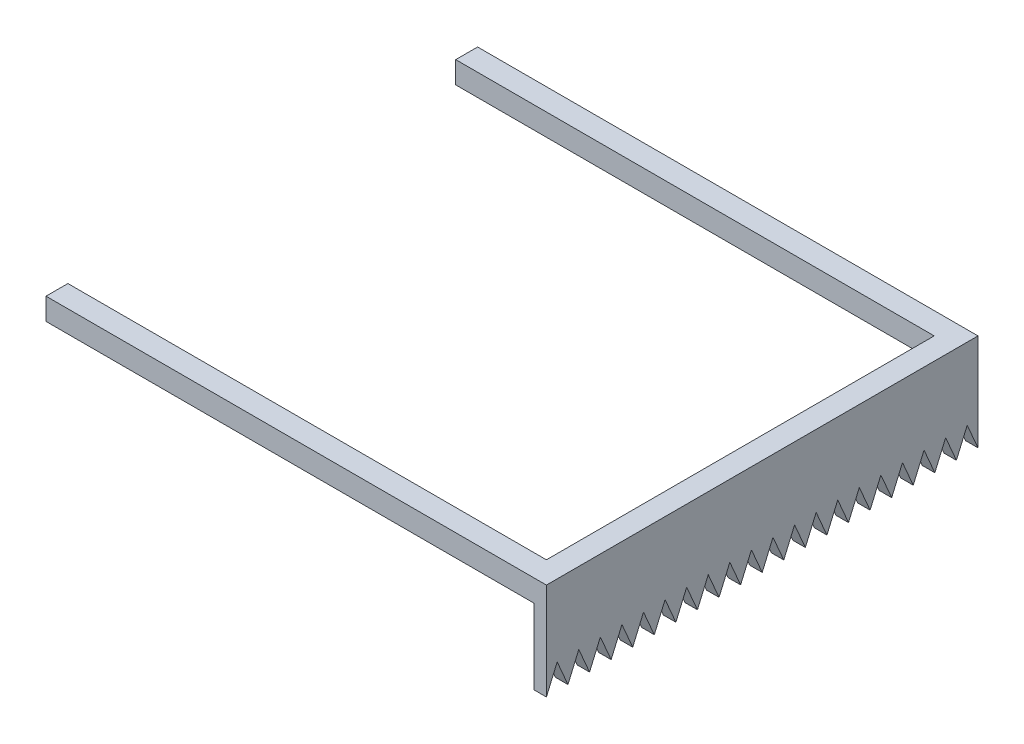
SolidWorks part; units mm, degrees
ref_plane "Front Plane" through (0, 0, 0) normal (0, 0, 1) x (1, 0, 0)
ref_plane "Top Plane" through (0, 0, 0) normal (0, 1, 0) x (1, 0, 0)
ref_plane "Right Plane" through (0, 0, 0) normal (1, 0, 0) x (0, 0, -1)
sketch "Sketch2" plane through (0, 0, 0) normal (1, 0, 0) x (0, 0, -1)
  line L0 (0, 35) -> (0, 0) construction
  line L1 (0, 0) -> (35, 0)
  line L2 (0, 0) -> (0, 35)
  line L3 (0, 35) -> (35, 35)
  line L4 (35, 0) -> (35, 35)
extrude "Boss-Extrude1" add sketch "Sketch2" along normal blind 800
sketch "Sketch3" plane through (0, 0, -35) normal (0, 0, -1) x (-1, 0, 0)
  line L0 (-800, 0) -> (0, 0) construction
  line L1 (-800, 35) -> (-765, 35)
  line L2 (-800, 35) -> (-800, 0)
  line L3 (-800, 0) -> (-765, 0)
  line L4 (-765, 35) -> (-765, 0)
extrude "Boss-Extrude2" add sketch "Sketch3" along normal up to surface (620 mm away)
sketch "Sketch5" plane through (800, 0, 0) normal (1, 0, 0) x (0, 0, -1)
  line L0 (655, 35) -> (0, 35) construction
  line L1 (655, 0) -> (690, 0)
  line L2 (655, 0) -> (655, 35)
  line L3 (655, 35) -> (690, 35)
  line L4 (690, 0) -> (690, 35)
extrude "Boss-Extrude3" add sketch "Sketch5" against normal up to surface (800 mm away) up to face at (0, 17.5, -17.5)
sketch "Sketch6" plane through (0, 0, 0) normal (0, -1, 0) x (1, 0, 0)
  line L0 (0, -690) -> (800, -690) construction
  line L1 (800, 0) -> (780, 0)
  line L2 (800, 0) -> (800, -690)
  line L3 (800, -690) -> (780, -690)
  line L4 (780, 0) -> (780, -690)
  dimension "D1" = 20
extrude "Boss-Extrude4" add sketch "Sketch6" along normal blind 120
sketch "Sketch7" plane through (800, 0, 0) normal (1, 0, 0) x (0, 0, -1)
  line L0 (0, -120) -> (17.25, -80)
  line L1 (17.25, -80) -> (34.5, -120)
  line L2 (690, -120) -> (0, -120) construction
  line L3 (34.5, -120) -> (0, -120)
  line L4 (0, -120) -> (690, -120) construction
  line L5 (17.25, -80) -> (17.25, -120) construction
  line L6 (34.5, -120) -> (51.75, -80)
  line L7 (51.75, -80) -> (69, -120)
  line L8 (69, -120) -> (34.5, -120)
  line L9 (69, -120) -> (86.25, -80)
  line L10 (86.25, -80) -> (103.5, -120)
  line L11 (103.5, -120) -> (69, -120)
  line L12 (103.5, -120) -> (120.75, -80)
  line L13 (120.75, -80) -> (138, -120)
  line L14 (138, -120) -> (103.5, -120)
  line L15 (138, -120) -> (155.25, -80)
  line L16 (155.25, -80) -> (172.5, -120)
  line L17 (172.5, -120) -> (138, -120)
  line L18 (172.5, -120) -> (189.75, -80)
  line L19 (189.75, -80) -> (207, -120)
  line L20 (207, -120) -> (172.5, -120)
  line L21 (207, -120) -> (224.25, -80)
  line L22 (224.25, -80) -> (241.5, -120)
  line L23 (241.5, -120) -> (207, -120)
  line L24 (241.5, -120) -> (258.75, -80)
  line L25 (258.75, -80) -> (276, -120)
  line L26 (276, -120) -> (241.5, -120)
  line L27 (276, -120) -> (293.25, -80)
  line L28 (293.25, -80) -> (310.5, -120)
  line L29 (310.5, -120) -> (276, -120)
  line L30 (310.5, -120) -> (327.75, -80)
  line L31 (327.75, -80) -> (345, -120)
  line L32 (345, -120) -> (310.5, -120)
  line L33 (345, -120) -> (362.25, -80)
  line L34 (362.25, -80) -> (379.5, -120)
  line L35 (379.5, -120) -> (345, -120)
  line L36 (379.5, -120) -> (396.75, -80)
  line L37 (396.75, -80) -> (414, -120)
  line L38 (414, -120) -> (379.5, -120)
  line L39 (414, -120) -> (431.25, -80)
  line L40 (431.25, -80) -> (448.5, -120)
  line L41 (448.5, -120) -> (414, -120)
  line L42 (448.5, -120) -> (465.75, -80)
  line L43 (465.75, -80) -> (483, -120)
  line L44 (483, -120) -> (448.5, -120)
  line L45 (483, -120) -> (500.25, -80)
  line L46 (500.25, -80) -> (517.5, -120)
  line L47 (517.5, -120) -> (483, -120)
  line L48 (517.5, -120) -> (534.75, -80)
  line L49 (534.75, -80) -> (552, -120)
  line L50 (552, -120) -> (517.5, -120)
  line L51 (552, -120) -> (569.25, -80)
  line L52 (569.25, -80) -> (586.5, -120)
  line L53 (586.5, -120) -> (552, -120)
  line L54 (586.5, -120) -> (603.75, -80)
  line L55 (603.75, -80) -> (621, -120)
  line L56 (621, -120) -> (586.5, -120)
  line L57 (621, -120) -> (638.25, -80)
  line L58 (638.25, -80) -> (655.5, -120)
  line L59 (655.5, -120) -> (621, -120)
  line L60 (655.5, -120) -> (672.75, -80)
  line L61 (672.75, -80) -> (690, -120)
  line L62 (690, -120) -> (655.5, -120)
  line L63 (0, -120) -> (34.5, -120) construction
  line M62 (0, -120) -> (690, -120)
  dimension "D1" = 690
  dimension "D2" = 34.5
  dimension "D3" = 40
  dimension "D5" = 34.5
  dimension "D4" = 20
extrude "Cut-Extrude1" cut sketch "Sketch7" against normal through all contours L7 L6 M62 | L10 L9 M62 | L13 L12 M62 | L16 L15 M62 | L19 L18 M62 | L22 L21 M62 | L25 L24 M62 | L28 L27 M62 | L31 L30 M62 | L34 L33 M62 | L37 L36 M62 | L40 L39 M62 | L43 L42 M62 | L46 L45 M62 | L49 L48 M62 | L52 L51 M62 | L55 L54 M62 | L58 L57 M62 | L61 L60 M62 | L1 L3 L0
equation "\"D2@Sketch7\" = \"D1@Sketch7\"/20"
equation "\"D5@Sketch7\" = \"D2@Sketch7\""
